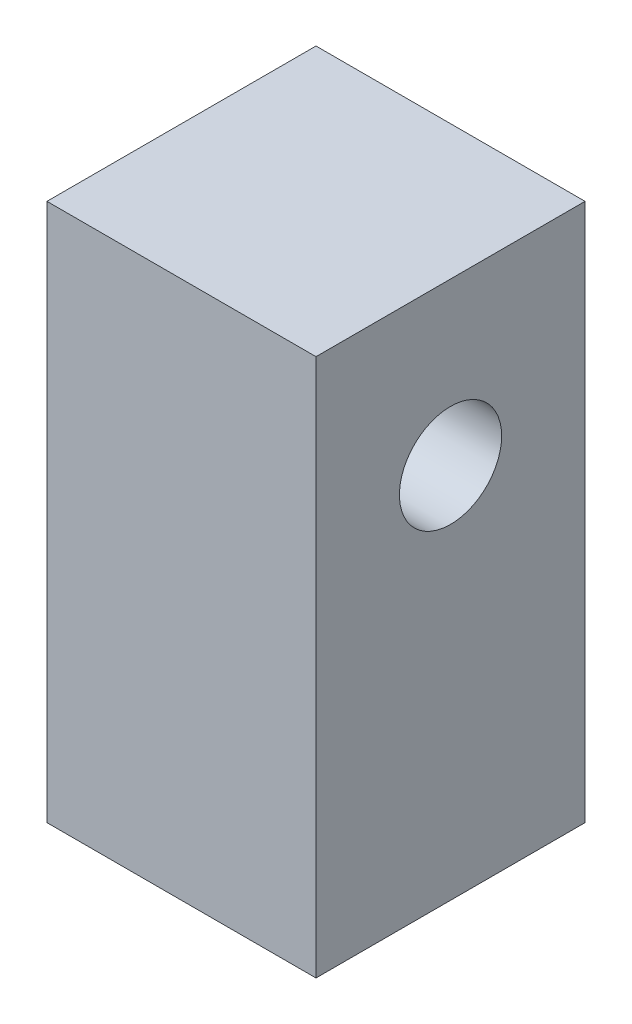
SolidWorks part; units mm, degrees
material "6061 Alloy"
ref_plane "Front Plane" through (0, 0, 0) normal (0, 0, 1) x (1, 0, 0)
ref_plane "Top Plane" through (0, 0, 0) normal (0, 1, 0) x (1, 0, 0)
ref_plane "Right Plane" through (0, 0, 0) normal (1, 0, 0) x (0, 0, -1)
sketch "Croquis1" plane through (0, 0, 0) normal (0, 1, 0) x (1, 0, 0)
  line L1 (6.35, -6.35) -> (-6.35, -6.35)
  line L2 (6.35, -6.35) -> (6.35, 6.35)
  line L3 (6.35, 6.35) -> (-6.35, 6.35)
  line L4 (-6.35, -6.35) -> (-6.35, 6.35)
  line L5 (6.35, -6.35) -> (-6.35, 6.35) construction
  line L6 (6.35, 6.35) -> (-6.35, -6.35) construction
  point P0 (0, 0)
  dimension "D1" = 12.7
extrude "Saliente-Extruir1" add sketch "Croquis1" along normal blind 25.4
sketch "Croquis2" plane through (6.35, 0, 0) normal (1, 0, 0) x (0, 0, -1)
  line L0 (0, 0) -> (0, 17.78) construction
  circle A0 centre (0, 17.78) radius 2.413
  dimension "D2" = 4.826
  dimension "D1" = 17.78
extrude "Cortar-Extruir1" cut sketch "Croquis2" against normal blind 25.4
